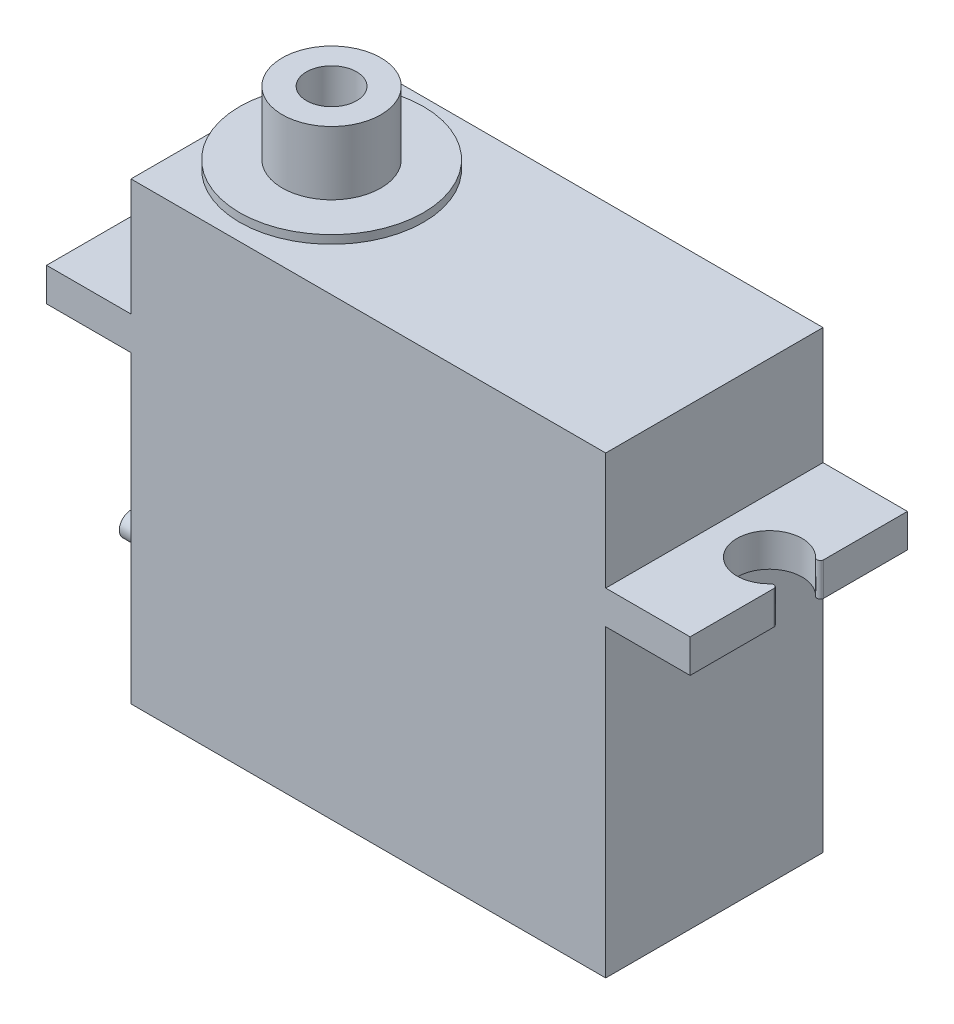
SolidWorks part; units mm, degrees
ref_plane "Plan de face" through (0, 0, 0) normal (0, 0, 1) x (1, 0, 0)
ref_plane "Plan de dessus" through (0, 0, 0) normal (0, 1, 0) x (1, 0, 0)
ref_plane "Plan de droite" through (0, 0, 0) normal (1, 0, 0) x (0, 0, -1)
sketch "Esquisse1" plane through (0, 0, 0) normal (0, 0, 1) x (1, 0, 0)
  line L0 (0, 0) -> (0, 3.4659) construction
  line L1 (-14.2, 9) -> (14.2, 9)
  line L2 (-14.2, 9) -> (-14.2, -18.2)
  line L3 (-14.2, -18.2) -> (14.2, -18.2)
  line L4 (14.2, 9) -> (14.2, -18.2)
  line L5 (-14.2, 2) -> (-19.25, 2)
  line L6 (-14.2, 2) -> (-14.2, 0)
  line L7 (-14.2, 0) -> (-19.25, 0)
  line L8 (-19.25, 2) -> (-19.25, 0)
  line L9 (14.2, 0) -> (19.25, 0)
  line L10 (19.25, 2) -> (19.25, 0)
  line L11 (14.2, 2) -> (19.25, 2)
  line L12 (14.2, 2) -> (14.2, 0)
  point P4 (0, 9)
  dimension "D1" = 2
  dimension "D2" = 38.5
  dimension "D3" = 28.4
  dimension "D4" = 27.2
  dimension "D5" = 7
extrude "Boss.-Extru.1" add sketch "Esquisse1" along normal mid plane 13
hole_wizard "Diamètre du perçage Ø3.9 (3.9)1" positions "Esquisse2" profile "Esquisse3" hole size "Ø3.9" standard "ISO" end condition up to next
sketch "Esquisse2" plane through (0, 2, 0) normal (0, 1, 0) x (1, 0, 0)
  line L0 (0, 0) -> (0, 4.6754) construction
  point P0 (-17.5, 0)
  point P12 (17.5, 0)
  dimension "D1" = 35
sketch "Esquisse3" plane through (-17.5, 2, 0) normal (1, 0, 0) x (0, 0, 1)
  line L0 (0, 0) -> (0, 2)
  line L1 (0, 2) -> (1.95, 2)
  line L2 (1.95, 2) -> (1.95, 0)
  line L5 (1.95, 0) -> (0, 0)
  line L11 (0, -6.35) -> (0, 107.95) construction
  dimension "Diamètre du perçage jusqu'au prochain" = 3.9
  dimension "Profondeur du perçage jusqu'au prochain" = 2
fillet "Congé1" radius 0.2 4 edges at (19.25, 1, -0.8602) (19.25, 1, 0.8602) (-19.25, 1, 0.8602) (-19.25, 1, -0.8602)
sketch "Esquisse6" plane through (0, 9, 0) normal (0, 1, 0) x (1, 0, 0)
  line L1 (-14.2, -6.5) -> (-14.2, 6.5) construction
  circle A0 centre (-8.7, 0) radius 5.5
  dimension "D1" = 11
extrude "Boss.-Extru.4" add sketch "Esquisse6" along normal blind 0.5 contours A0
sketch "Esquisse4" plane through (0, 9.5, 0) normal (0, 1, 0) x (1, 0, 0)
  circle A0 centre (-8.7, 0) radius 2.95
  dimension "D2" = 5.9
extrude "Boss.-Extru.2" add sketch "Esquisse4" along normal blind 3.8
hole_wizard "Diamètre du perçage Ø3.0 (3)1" positions "Esquisse10" profile "Esquisse11" hole size "Ø3.0" standard "ISO"
sketch "Esquisse10" plane through (0, 13.3, 0) normal (0, 1, 0) x (1, 0, 0)
  point P0 (-8.7, 0)
sketch "Esquisse11" plane through (-8.7, 13.3, 0) normal (1, 0, 0) x (0, 0, 1)
  line L0 (0, 0) -> (0, 6.9013)
  line L1 (0, 6.9013) -> (1.5, 6)
  line L2 (1.5, 6) -> (1.5, 0)
  line L5 (1.5, 0) -> (0, 0)
  line L10 (0, 6.9013) -> (-1.5, 6) construction
  line L11 (0, -6.35) -> (0, 107.95) construction
  dimension "Diamètre du perçage" = 3
  dimension "Profondeur du perçage" = 6
  dimension "Angle de pointe" = 118
sketch "Esquisse8" plane through (-14.2, 0, 0) normal (-1, 0, 0) x (0, 0, 1)
  line L1 (-3.1, -12) -> (3.1, -12)
  line L2 (-3.1, -12) -> (-3.1, -15.7)
  line L3 (-3.1, -15.7) -> (3.1, -15.7)
  line L4 (3.1, -12) -> (3.1, -15.7)
  point P4 (0, -12)
  dimension "D1" = 3.7
  dimension "D2" = 6.2
  dimension "D3" = 12
extrude "Boss.-Extru.5" add sketch "Esquisse8" along normal blind 3
sketch "Esquisse9" plane through (-17.2, 0, 0) normal (-1, 0, 0) x (0, 0, 1)
  line L0 (0, 0) -> (0, -6.5483) construction
  line L2 (-1.95, 0) -> (1.95, 0) construction
  line L4 (-3.1, -13.85) -> (3.1, -13.85) construction
  line L5 (-3.1, -12) -> (-3.1, -15.7) construction
  line L6 (3.1, -15.7) -> (3.1, -12) construction
  circle A3 centre (0, -13.85) radius 0.7
  circle A4 centre (-1.5, -13.85) radius 0.7
  circle A5 centre (1.5, -13.85) radius 0.7
  dimension "D1" = 1.4
  dimension "D2" = 1.5
extrude "Boss.-Extru.6" add sketch "Esquisse9" along normal blind 2
